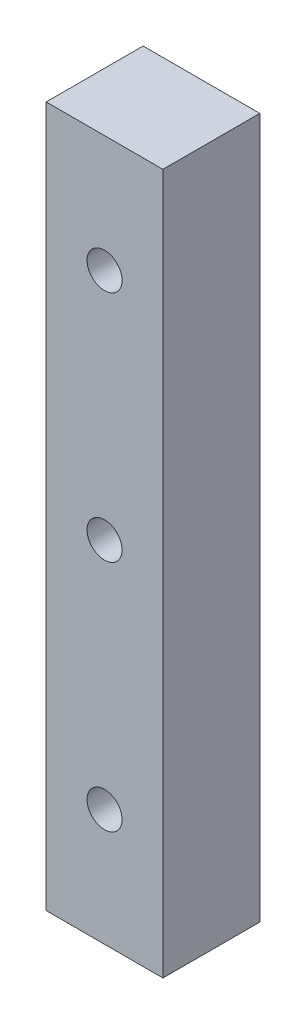
SolidWorks part; units mm, degrees
ref_plane "Plan de face" through (0, 0, 0) normal (0, 0, 1) x (1, 0, 0)
ref_plane "Plan de dessus" through (0, 0, 0) normal (0, 1, 0) x (1, 0, 0)
ref_plane "Plan de droite" through (0, 0, 0) normal (1, 0, 0) x (0, 0, -1)
sketch "Esquisse1" plane through (0, 0, 0) normal (0, 0, 1) x (1, 0, 0)
  line L1 (-5, -30) -> (5, -30)
  line L2 (-5, -30) -> (-5, 30)
  line L3 (-5, 30) -> (5, 30)
  line L4 (5, -30) -> (5, 30)
  line L5 (-5, -30) -> (5, 30) construction
  line L6 (-5, 30) -> (5, -30) construction
  point P0 (0, 0)
  dimension "D1" = 10
  dimension "D2" = 60
extrude "Extrusion1" add sketch "Esquisse1" along normal blind 8.3
sketch "Esquisse2" plane through (0, 0, 8.3) normal (0, 0, 1) x (1, 0, 0)
  circle A0 centre (0, -20) radius 1.5
  circle A1 centre (0, 0) radius 1.5
  circle A2 centre (0, 20) radius 1.5
extrude "Enlèv. mat.-Extru.1" cut sketch "Esquisse2" against normal blind 10
